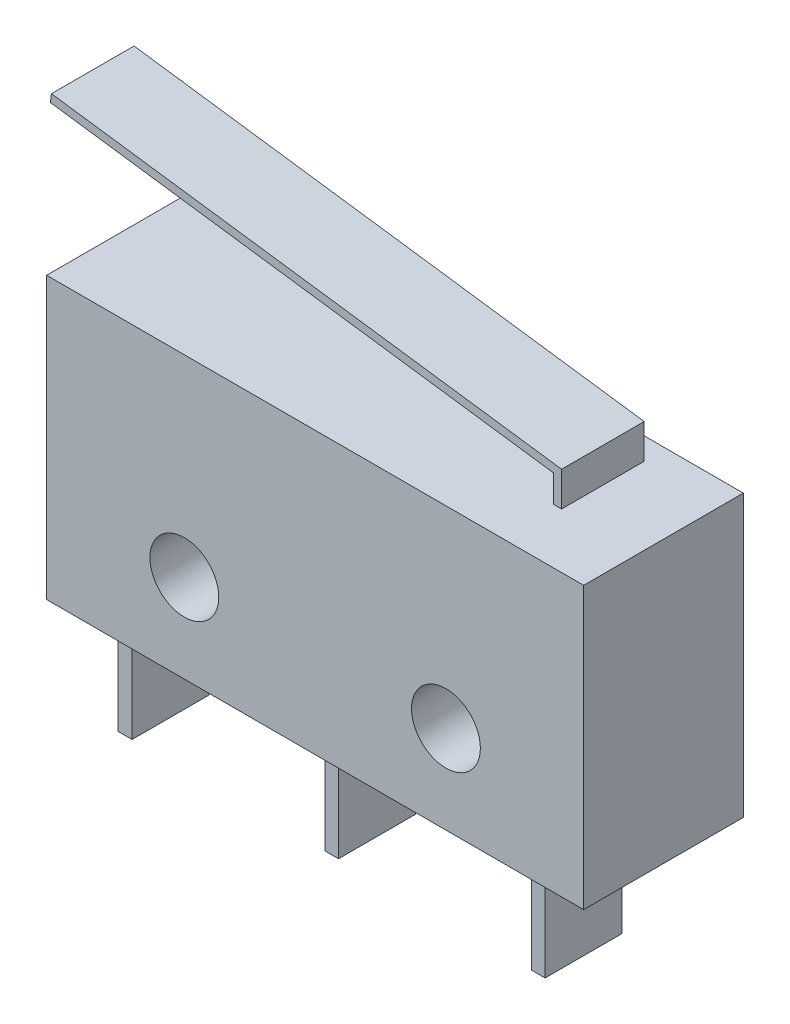
SolidWorks part; units mm, degrees
ref_plane "Front Plane" through (0, 0, 0) normal (0, 0, 1) x (1, 0, 0)
ref_plane "Top Plane" through (0, 0, 0) normal (0, 1, 0) x (1, 0, 0)
ref_plane "Right Plane" through (0, 0, 0) normal (1, 0, 0) x (0, 0, -1)
ref_plane "Plane1" through (0, 0, 5) normal (0, 0, 1) x (1, 0, 0)
sketch "Sketch1" plane through (0, 0, 5) normal (0, 0, 1) x (1, 0, 0)
  line L0 (-0.1659, -12.644) -> (-0.1659, -2.444)
  line L1 (-0.1659, -2.444) -> (-19.6659, -2.444)
  line L2 (-19.6659, -2.444) -> (-19.6659, -12.644)
  line L3 (-19.6659, -12.644) -> (-0.1659, -12.644)
  dimension "D1" = 19.5
  dimension "D2" = 10.2
extrude "Boss-Extrude1" add sketch "Sketch1" against normal blind 5.8
sketch "Sketch4" plane through (0, -12.644, 0) normal (0, -1, 0) x (1, 0, 0)
  line L0 (-9.4159, 1.85) -> (-9.9159, 1.85)
  line L1 (-9.9159, 1.85) -> (-9.9159, 4.65)
  line L2 (-9.9159, 4.65) -> (-9.4159, 4.65)
  line L3 (-9.4159, 4.65) -> (-9.4159, 1.85)
extrude "Boss-Extrude4" add sketch "Sketch4" along normal blind 3.2
sketch "Sketch5" plane through (0, -12.644, 0) normal (0, -1, 0) x (1, 0, 0)
  line L0 (-16.9159, 1.85) -> (-17.4159, 1.85)
  line L1 (-17.4159, 1.85) -> (-17.4159, 4.65)
  line L2 (-17.4159, 4.65) -> (-16.9159, 4.65)
  line L3 (-16.9159, 4.65) -> (-16.9159, 1.85)
extrude "Boss-Extrude5" add sketch "Sketch5" along normal blind 3.2
sketch "Sketch6" plane through (0, -12.644, 0) normal (0, -1, 0) x (1, 0, 0)
  line L0 (-1.9159, 1.85) -> (-2.4159, 1.85)
  line L1 (-2.4159, 1.85) -> (-2.4159, 4.65)
  line L2 (-2.4159, 4.65) -> (-1.9159, 4.65)
  line L3 (-1.9159, 4.65) -> (-1.9159, 1.85)
extrude "Boss-Extrude6" add sketch "Sketch6" along normal blind 3.2
hole_wizard "Ø2.5 (2.5) Diameter Hole1" positions "Sketch8" profile "Sketch7" hole size "Ø2.5" standard "ANSI Metric"
sketch "Sketch8" plane through (0, 0, -0.8) normal (0, 0, -1) x (-1, 0, 0)
  line L0 (9.9159, -2.444) -> (9.9159, 2.9031) construction
  line L1 (0.1659, -2.444) -> (19.6659, -2.444) construction
  point P0 (14.6659, -9.444)
  point P1 (5.1659, -9.444)
  dimension "D1" = 6.4
  dimension "D2" = 4.75
  dimension "D3" = 6.4
  dimension "D4" = 4.75
sketch "Sketch7" plane through (-14.6659, -9.444, -0.8) normal (1, 0, 0) x (0, 1, 0)
  line L0 (0, 0) -> (0, 10.7511)
  line L1 (0, 10.7511) -> (1.25, 10)
  line L2 (1.25, 10) -> (1.25, 0)
  line L5 (1.25, 0) -> (0, 0)
  line L10 (0, 10.7511) -> (-1.25, 10) construction
  line L11 (0, -6.35) -> (0, 107.95) construction
  dimension "Hole Dia." = 2.5
  dimension "Hole Depth" = 10
  dimension "Drill Angle" = 118
sketch "Sketch9" plane through (0, 0, 0) normal (0, 0, 1) x (1, 0, 0)
  line L0 (-2.9659, -1.194) -> (-2.9659, -2.444)
  line L1 (-2.9659, -1.194) -> (-21.4916, 1.3532)
  line L2 (-21.4916, 1.3532) -> (-21.5324, 1.056)
  line L3 (-21.5324, 1.056) -> (-3.2659, -1.4556)
  line L5 (-0.1659, -2.444) -> (-19.6659, -2.444) construction
  line L6 (-2.9659, -2.444) -> (-3.2659, -2.444)
  line L7 (-3.2659, -2.444) -> (-3.2659, -1.4556)
  circle A0 centre (-14.6659, -9.444) radius 1.25 construction
  dimension "D1" = 18.7
  dimension "D2" = 1.25
  dimension "D3" = 0.3
  dimension "D4" = 2.8
  dimension "D5" = 10.5
  dimension "D6" = 0.3
extrude "Boss-Extrude7" add sketch "Sketch9" along normal blind 3
